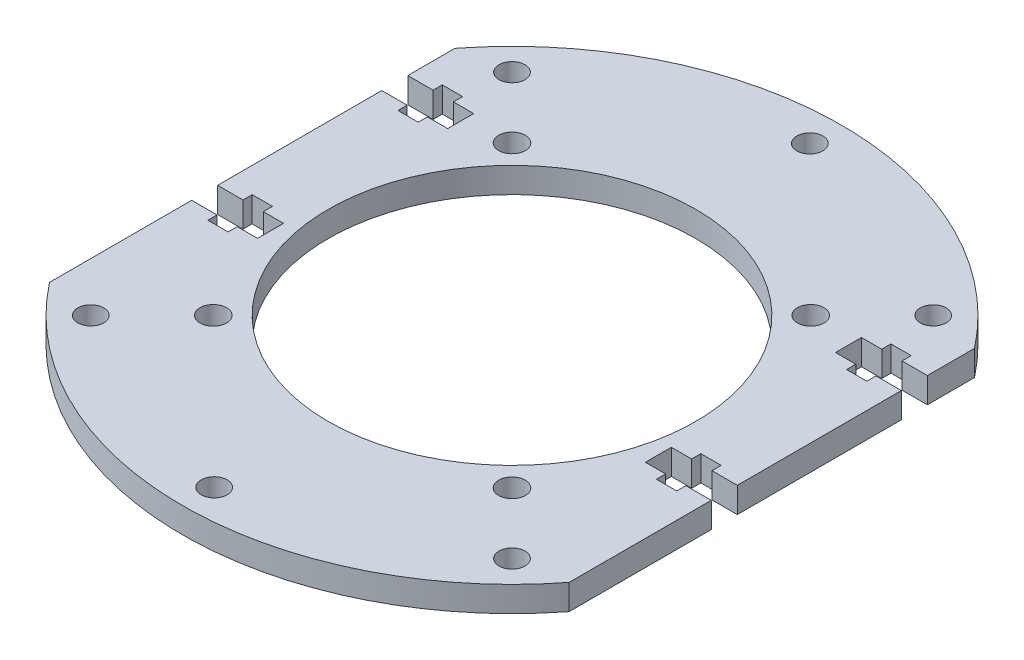
SolidWorks part; units mm, degrees
ref_plane "前视基准面" through (0, 0, 0) normal (0, 0, 1) x (1, 0, 0)
ref_plane "上视基准面" through (0, 0, 0) normal (0, 1, 0) x (1, 0, 0)
ref_plane "右视基准面" through (0, 0, 0) normal (1, 0, 0) x (0, 0, -1)
sketch "草图1" plane through (0, 0, 0) normal (0, 1, 0) x (1, 0, 0)
  line L0 (37, -9.55) -> (37, -11)
  line L1 (23.57, 23.57) -> (-23.57, 23.57) construction
  line L2 (23.57, 23.57) -> (23.57, -23.57) construction
  line L3 (23.57, -23.57) -> (-23.57, -23.57) construction
  line L4 (-23.57, 23.57) -> (-23.57, -23.57) construction
  line L5 (37, -11) -> (33.8, -11)
  line L6 (33.8, -11) -> (33.8, -9.55)
  line L7 (33.8, -5.45) -> (33.8, -4)
  line L8 (37, -4) -> (37, -5.45)
  line L9 (33.8, -4) -> (37, -4)
  line L12 (37, -4) -> (37, 26) construction
  line L13 (37, 20.45) -> (37, 19)
  line L14 (37, 19) -> (33.8, 19)
  line L15 (33.8, 19) -> (33.8, 20.45)
  line L16 (33.8, 24.55) -> (33.8, 26)
  line L17 (37, 26) -> (37, 24.55)
  line L18 (33.8, 26) -> (37, 26)
  line L21 (0, -47) -> (0, -44.95) construction
  line L22 (-37, -4) -> (-37, 26) construction
  line L25 (-33.8, 26) -> (-37, 26)
  line L26 (-37, 26) -> (-37, 24.55)
  line L27 (-33.8, 24.55) -> (-33.8, 26)
  line L28 (-33.8, 19) -> (-33.8, 20.45)
  line L29 (-37, 19) -> (-33.8, 19)
  line L30 (-37, 20.45) -> (-37, 19)
  line L33 (-33.8, -4) -> (-37, -4)
  line L34 (-37, -4) -> (-37, -5.45)
  line L35 (-33.8, -5.45) -> (-33.8, -4)
  line L36 (-33.8, -11) -> (-33.8, -9.55)
  line L37 (-37, -11) -> (-33.8, -11)
  line L38 (-37, -9.55) -> (-37, -11)
  line L39 (37, 24.55) -> (41, 24.55)
  line L40 (41, 24.55) -> (41, 20.45)
  line L41 (41, 20.45) -> (37, 20.45)
  line L42 (33.8, 24.55) -> (30.6, 24.55)
  line L43 (30.6, 24.55) -> (30.6, 20.45)
  line L44 (30.6, 20.45) -> (33.8, 20.45)
  line L45 (37, -5.45) -> (41, -5.45)
  line L46 (41, -5.45) -> (41, -9.55)
  line L47 (41, -9.55) -> (37, -9.55)
  line L48 (33.8, -9.55) -> (30.6, -9.55)
  line L49 (30.6, -9.55) -> (30.6, -5.45)
  line L50 (30.6, -5.45) -> (33.8, -5.45)
  line L51 (-37, 24.55) -> (-41, 24.55)
  line L52 (-41, 24.55) -> (-41, 20.45)
  line L53 (-41, 20.45) -> (-37, 20.45)
  line L54 (-37, -5.45) -> (-41, -5.45)
  line L55 (-41, -5.45) -> (-41, -9.55)
  line L56 (-41, -9.55) -> (-37, -9.55)
  line L57 (-33.8, -5.45) -> (-30.6, -5.45)
  line L58 (-30.6, -5.45) -> (-30.6, -9.55)
  line L59 (-30.6, -9.55) -> (-33.8, -9.55)
  line L60 (-33.8, 24.55) -> (-30.6, 24.55)
  line L61 (-30.6, 24.55) -> (-30.6, 20.45)
  line L62 (-30.6, 20.45) -> (-33.8, 20.45)
  circle A0 centre (0, 0) radius 29
  circle A1 centre (0, 0) radius 52
  circle A2 centre (47, 0) radius 2.05
  circle A3 centre (33.234, -33.234) radius 2.05
  circle A4 centre (0, -47) radius 2.05
  circle A5 centre (-33.234, -33.234) radius 2.05
  circle A6 centre (-47, 0) radius 2.05
  circle A7 centre (-33.234, 33.234) radius 2.05
  circle A8 centre (0, 47) radius 2.05
  circle A9 centre (33.234, 33.234) radius 2.05
  circle A10 centre (0, 0) radius 43 construction
  circle A11 centre (-23.57, 23.57) radius 2.1
  circle A12 centre (-23.57, -23.57) radius 2.1
  circle A13 centre (23.57, -23.57) radius 2.1
  circle A14 centre (23.57, 23.57) radius 2.1
  circle A15 centre (0, 0) radius 25 construction
  circle A16 centre (0, 0) radius 9.5 construction
  point P6 (52, 0)
  point P9 (43, 0)
  dimension "D1" = 58
  dimension "D2" = 86
  dimension "D3" = 4
  dimension "D4" = 4.1
  dimension "D6" = 30
  dimension "D7" = 5
  dimension "D5" = 8
extrude "凸台-拉伸1" add sketch "草图1" along normal blind 4
sketch "草图2" plane through (0, 4, 0) normal (0, 1, 0) x (1, 0, 0)
  line L1 (-41, -55.0176) -> (41, -55.0176)
  line L2 (-41, -55.0176) -> (-41, 55.0176)
  line L3 (-41, 55.0176) -> (41, 55.0176)
  line L4 (41, -55.0176) -> (41, 55.0176)
  line L5 (-41, -55.0176) -> (41, 55.0176) construction
  line L6 (-41, 55.0176) -> (41, -55.0176) construction
  point P0 (0, 0)
  dimension "D1" = 82
extrude "切除-拉伸-薄壁1" cut sketch "草图2" against normal blind 4 thin
